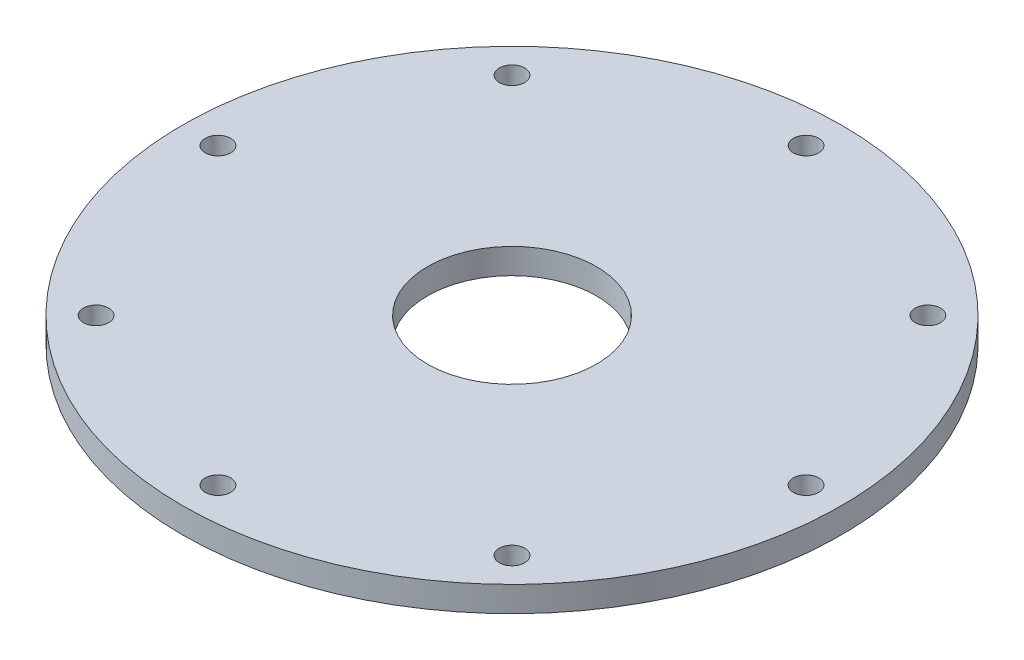
SolidWorks part; units mm, degrees
ref_plane "前视基准面" through (0, 0, 0) normal (0, 0, 1) x (1, 0, 0)
ref_plane "上视基准面" through (0, 0, 0) normal (0, 1, 0) x (1, 0, 0)
ref_plane "右视基准面" through (0, 0, 0) normal (1, 0, 0) x (0, 0, -1)
sketch "草图1" plane through (0, 0, 0) normal (0, 1, 0) x (1, 0, 0)
  circle A0 centre (0, 0) radius 50
  circle A1 centre (0, 0) radius 195
  dimension "D1" = 390
  dimension "D2" = 100
extrude "凸台-拉伸1" add sketch "草图1" along normal blind 15
sketch "草图2" plane through (0, 15, 0) normal (0, 1, 0) x (1, 0, 0)
  circle A0 centre (0, 0) radius 174 construction
  circle A1 centre (-174, 0) radius 7.5
  circle A2 centre (-123.0366, 123.0366) radius 7.5
  circle A3 centre (0, 174) radius 7.5
  circle A4 centre (123.0366, 123.0366) radius 7.5
  circle A5 centre (174, 0) radius 7.5
  circle A6 centre (123.0366, -123.0366) radius 7.5
  circle A7 centre (0, -174) radius 7.5
  circle A8 centre (-123.0366, -123.0366) radius 7.5
  dimension "D1" = 348
  dimension "D2" = 15
  dimension "D3" = 8
extrude "切除-拉伸1" cut sketch "草图2" against normal up to next
